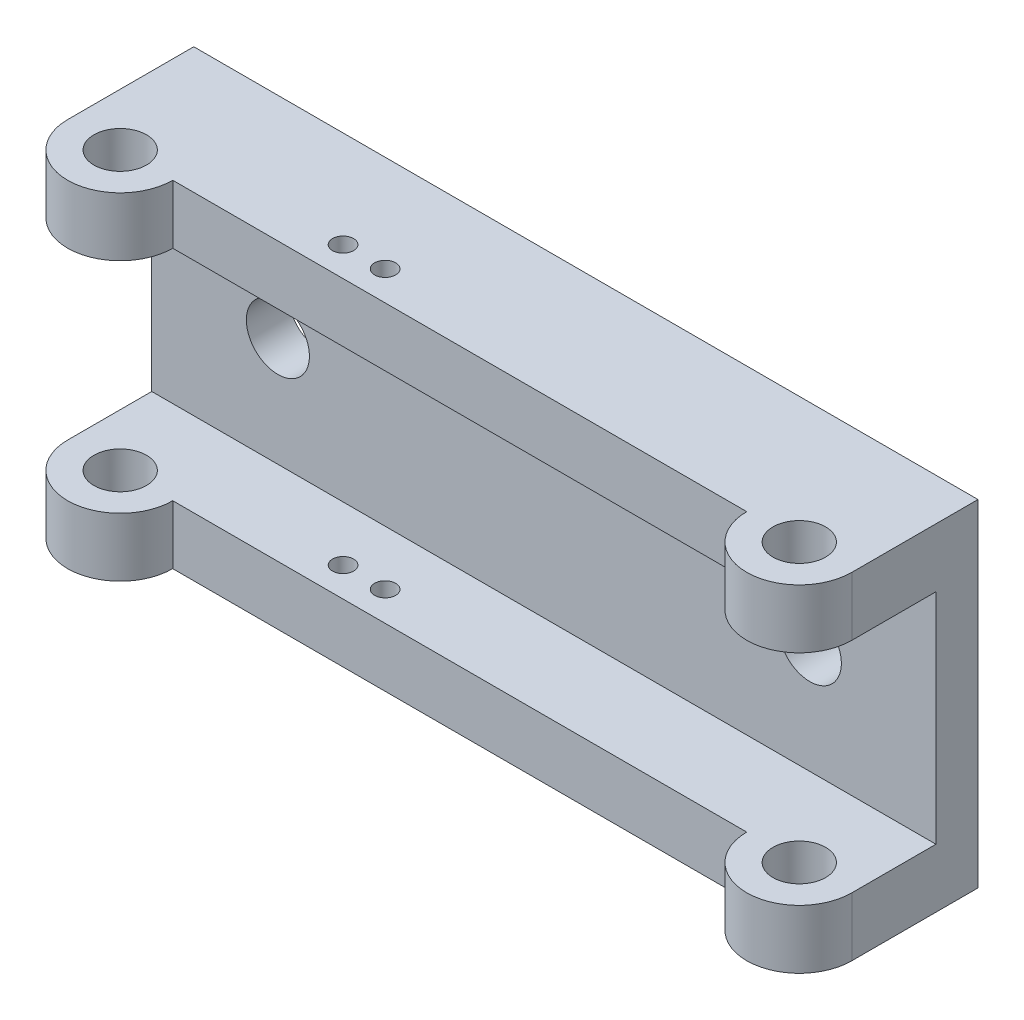
SolidWorks part; units mm, degrees
material "7075-T6 (SN)"
ref_plane "X-Y Datum" through (0, 0, 0) normal (0, 0, 1) x (1, 0, 0)
ref_plane "X-Z Datum" through (0, 0, 0) normal (0, 1, 0) x (1, 0, 0)
ref_plane "Y-Z Datum" through (0, 0, 0) normal (1, 0, 0) x (0, 0, -1)
sketch "Sketch2" plane through (0, 0, 0) normal (1, 0, 0) x (0, 0, -1)
  line L0 (0, -25.4) -> (0, 25.4)
  line L1 (0, 25.4) -> (-63.5, 25.4)
  line L2 (-63.5, 25.4) -> (-63.5, 16.51)
  line L3 (-63.5, 16.51) -> (-6.35, 16.51)
  line L4 (-6.35, 16.51) -> (-6.35, -16.51)
  line L6 (-6.35, 0) -> (0, 0) construction
  line L7 (0, -25.4) -> (-63.5, -25.4)
  line L8 (-63.5, -25.4) -> (-63.5, -16.51)
  line L9 (-63.5, -16.51) -> (-6.35, -16.51)
  dimension "D1" = 16.51
  dimension "D2" = 6.35
  dimension "D3" = 57.15
  dimension "D4" = 8.89
extrude "Boss-Extrude1" add sketch "Sketch2" along normal blind 118.4275
sketch "Sketch3" plane through (0, 0, 0) normal (0, 1, 0) x (1, 0, 0)
  line L0 (0, 0) -> (0, -63.5) construction
  line L1 (118.4275, -6.35) -> (0, -6.35) construction
  line L2 (15.875, -19.05) -> (102.5525, -19.05)
  line L5 (0, -63.5) -> (0, -19.05)
  line L7 (110.49, -19.05) -> (7.9375, -19.05) construction
  line L9 (118.4275, -63.5) -> (0, -63.5)
  line L10 (118.4275, -63.5) -> (118.4275, -19.05)
  line L12 (110.49, -19.05) -> (118.4275, -19.05) construction
  circle A0 centre (7.9375, -19.05) radius 3.9688
  circle A1 centre (110.49, -19.05) radius 3.9688
  circle A2 centre (7.9375, -52.3875) radius 15.0812 construction
  arc A3 (7.9375, -52.3875) -> (33.4755, -40.4789) centre (7.9375, -19.05) ccw construction
  circle A4 centre (33.4755, -40.4789) radius 15.0812 construction
  arc A5 (0, -19.05) -> (15.875, -19.05) centre (7.9375, -19.05) ccw
  arc A7 (102.5525, -19.05) -> (118.4275, -19.05) centre (110.49, -19.05) ccw
  circle A8 centre (37.1475, -14.605) radius 1.5875
  circle A9 centre (43.4975, -14.605) radius 1.5875
  dimension "D1" = 7.9375
  dimension "D2" = 7.9375
  dimension "D6" = 30.1625
  dimension "D10" = 7.9375
  dimension "D11" = 7.9375
  dimension "D7" = 3.175
  dimension "D3" = 6.35
  dimension "D4" = 7.9375
  dimension "D5" = 12.7
  dimension "D8" = 50
  dimension "D9" = 4.445
  dimension "D12" = 29.21
extrude "Cut-Extrude1" cut sketch "Sketch3" against normal up to surface and the other way up to surface up to face at (59.2137, -25.4, 31.75) other way up to face at (59.2137, 25.4, 31.75)
sketch "Sketch4" plane through (0, 0, 0) normal (0, 0, 1) x (1, 0, 0)
  line L0 (0, -25.4) -> (0, 25.4) construction
  line L1 (118.4275, 16.51) -> (118.4275, -16.51) construction
  circle A0 centre (19.05, 0) radius 4.7625
  circle A1 centre (99.3775, 0) radius 4.7625
  dimension "D1" = 9.525
  dimension "D2" = 19.05
  dimension "D3" = 19.05
extrude "Cut-Extrude2" cut sketch "Sketch4" along normal up to surface (6.35 mm away) up to face at (59.2137, 0, 6.35)
